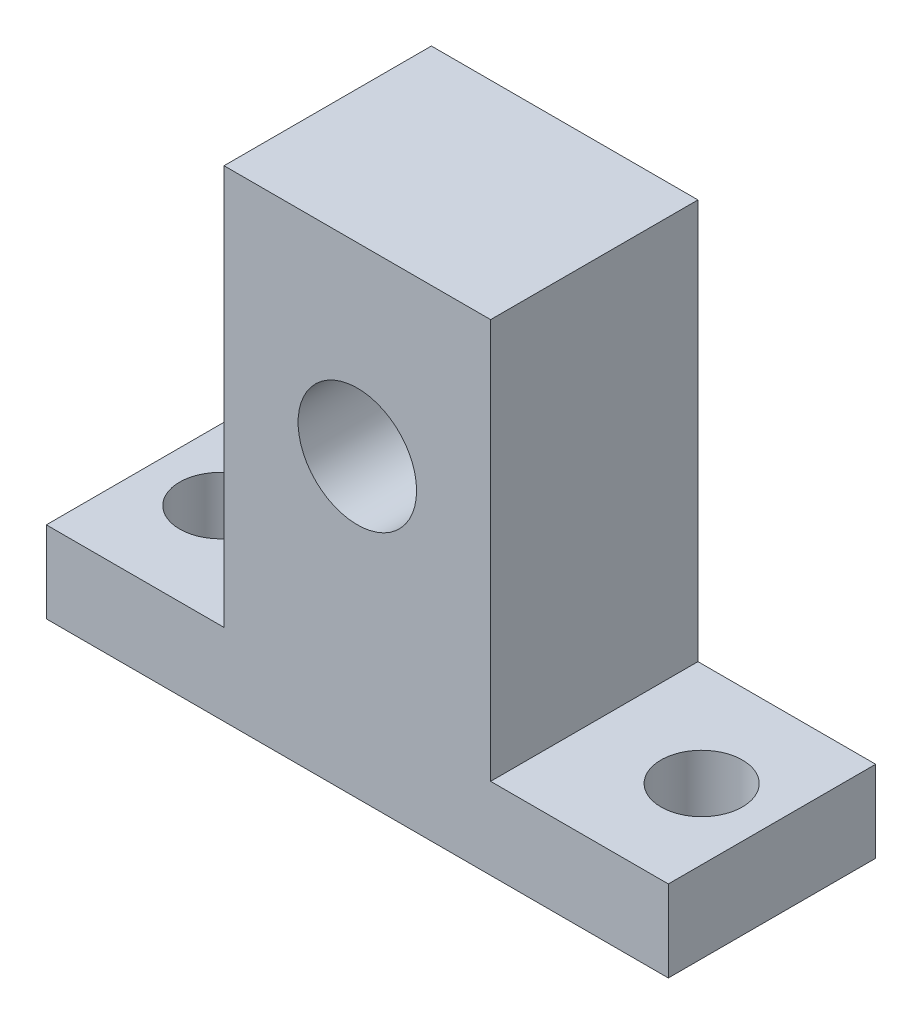
SolidWorks part; units mm, degrees
ref_plane "前视基准面" through (0, 0, 0) normal (0, 0, 1) x (1, 0, 0)
ref_plane "上视基准面" through (0, 0, 0) normal (0, 1, 0) x (1, 0, 0)
ref_plane "右视基准面" through (0, 0, 0) normal (1, 0, 0) x (0, 0, -1)
sketch "草图1" plane through (0, 0, 0) normal (0, 0, 1) x (1, 0, 0)
  line L0 (-21, -10.75) -> (-9, -10.75)
  line L1 (-21, -16.25) -> (21, -16.25)
  line L2 (-21, -16.25) -> (-21, -10.75)
  line L3 (-9, 16.25) -> (9, 16.25)
  line L4 (21, -16.25) -> (21, -10.75)
  line L5 (-21, -16.25) -> (9, 6.9643) construction
  line L6 (-9, 6.9643) -> (21, -16.25) construction
  line L7 (-9, -10.75) -> (-9, 16.25)
  line L8 (0, 16.25) -> (0, -16.25) construction
  line L9 (21, -10.75) -> (9, -10.75)
  line L10 (9, -10.75) -> (9, 16.25)
  circle A0 centre (0, 3.75) radius 4
  point P0 (0, 0)
  dimension "D1" = 8
  dimension "D5" = 20
  dimension "D2" = 42
  dimension "D3" = 5.5
  dimension "D4" = 9
extrude "凸台-拉伸1" add sketch "草图1" along normal blind 14
sketch "草图2" plane through (0, -10.75, 0) normal (0, 1, 0) x (1, 0, 0)
  line L0 (-21, -7) -> (21, -7) construction
  line L1 (-21, -14) -> (-21, 0) construction
  line L2 (21, -14) -> (21, 0) construction
  circle A0 centre (-16.25, -7) radius 2.75
  circle A1 centre (16.25, -7) radius 2.75
  dimension "D1" = 5.5
  dimension "D2" = 5.5
  dimension "D3" = 4.75
  dimension "D4" = 4.75
extrude "切除-拉伸1" cut sketch "草图2" against normal blind 14
sketch "草图3" plane through (0, -10.75, 0) normal (0, 1, 0) x (1, 0, 0)
  line L4 (-9, 0) -> (-21, 0)
  line L5 (-21, 0) -> (-21, -14)
  line L6 (-21, -14) -> (-9, -14)
  line L7 (-9, -14) -> (-9, 0)
  line L8 (-9, 0) -> (-21, 0)
  line L9 (-21, 0) -> (-21, -14)
  line L10 (-21, -14) -> (-9, -14)
  line L11 (-9, -14) -> (-9, 0)
  dimension "D1" = 0
extrude "切除-拉伸2" [suppressed] cut sketch "草图3" against normal blind 10
